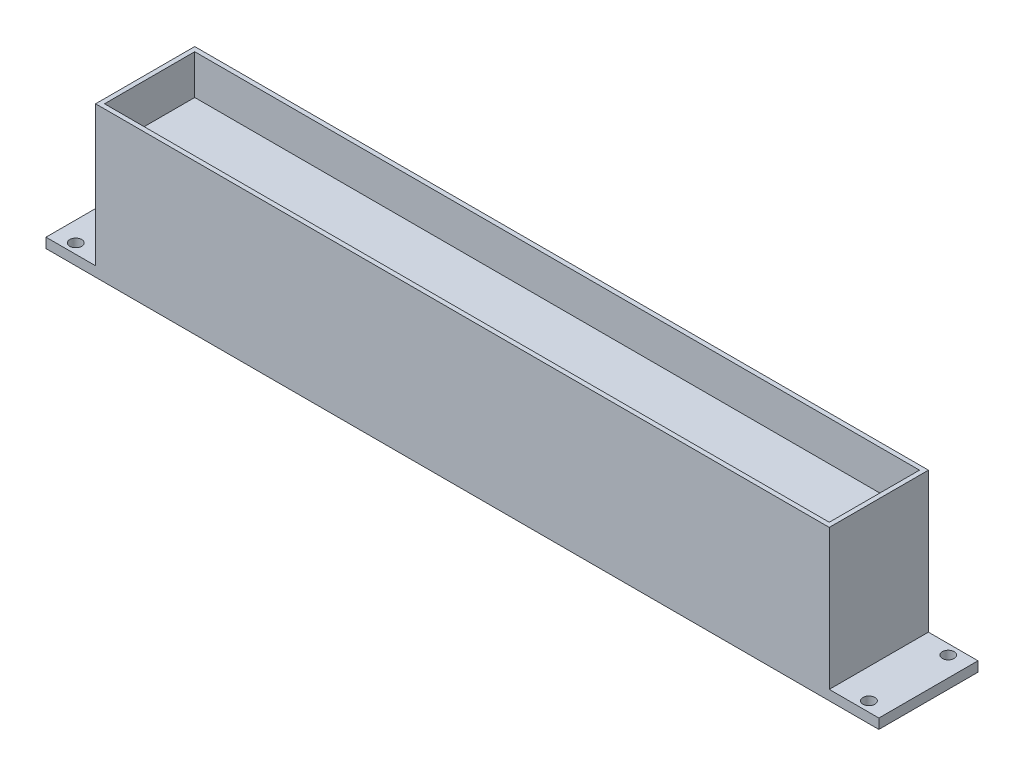
SolidWorks part; units mm, degrees
ref_plane "Front Plane" through (0, 0, 0) normal (0, 0, 1) x (1, 0, 0)
ref_plane "Top Plane" through (0, 0, 0) normal (0, 1, 0) x (1, 0, 0)
ref_plane "Right Plane" through (0, 0, 0) normal (1, 0, 0) x (0, 0, -1)
sketch "Sketch1" plane through (0, 0, 0) normal (0, 1, 0) x (1, 0, 0)
  line L0 (-200, -20) -> (-210, -20) construction
  line L1 (-210, -25) -> (210, -25)
  line L2 (-210, -25) -> (-210, 25)
  line L3 (-210, 25) -> (210, 25)
  line L4 (210, -25) -> (210, 25)
  line L5 (-210, -25) -> (210, 25) construction
  line L6 (-210, 25) -> (210, -25) construction
  line L7 (200, -20) -> (210, -20) construction
  line L8 (-200, -20) -> (-200, -25) construction
  line L9 (-200, 20) -> (-200, 25) construction
  line L10 (0, -55) -> (0, 55) construction
  circle A0 centre (-200, -20) radius 3
  circle A1 centre (200, -20) radius 3
  circle A2 centre (-200, 20) radius 3
  circle A3 centre (200, 20) radius 3
  point P0 (0, 0)
  dimension "D4" = 6
  dimension "D1" = 420
  dimension "D2" = 50
  dimension "D3" = 400
  dimension "D5" = 40
extrude "Boss-Extrude1" add sketch "Sketch1" along normal blind 75.75
sketch "Sketch2" plane through (0, 75.75, 0) normal (0, 1, 0) x (1, 0, 0)
  line L1 (-182.75, -22.75) -> (182.75, -22.75)
  line L2 (-182.75, -22.75) -> (-182.75, 22.75)
  line L3 (-182.75, 22.75) -> (182.75, 22.75)
  line L4 (182.75, -22.75) -> (182.75, 22.75)
  line L5 (-182.75, -22.75) -> (182.75, 22.75) construction
  line L6 (-182.75, 22.75) -> (182.75, -22.75) construction
  point P0 (0, 0)
  dimension "D1" = 365.5
  dimension "D2" = 45.5
extrude "Cut-Extrude1" cut sketch "Sketch2" against normal blind 20
sketch "Sketch3" plane through (0, 75.75, 0) normal (0, 1, 0) x (1, 0, 0)
  line L0 (-210, -25) -> (210, -25) construction
  line L1 (-185, -25) -> (-210, -25)
  line L2 (-185, -25) -> (-185, 25)
  line L3 (-185, 25) -> (-210, 25)
  line L4 (-210, -25) -> (-210, 25)
  line L5 (-185, 8.9181) -> (-182.75, 8.9181) construction
  line L6 (-182.75, 22.75) -> (-182.75, -22.75) construction
  line L7 (-170.3614, 22.75) -> (-170.3614, 25) construction
  line L8 (182.75, 22.75) -> (-182.75, 22.75) construction
  line L9 (210, 25) -> (-210, 25) construction
extrude "Cut-Extrude2" cut sketch "Sketch3" against normal offset from surface (70.75 mm away) 5 up to face at (-200, 0, -17)
mirror "Mirror1" about plane through (0, 0, 0) normal (1, 0, 0) of "Cut-Extrude2"
